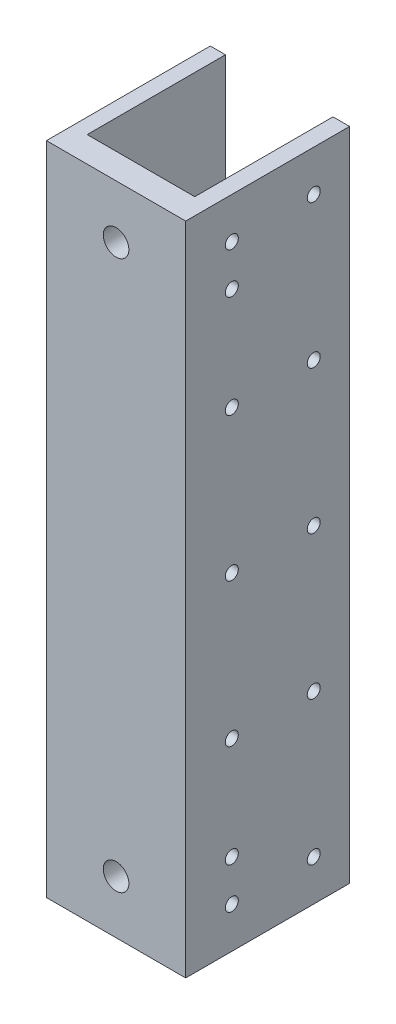
SolidWorks part; units mm, degrees
material "6061-T6 (SS)"
ref_plane "Front Plane" through (0, 0, 0) normal (0, 0, 1) x (1, 0, 0)
ref_plane "Top Plane" through (0, 0, 0) normal (0, 1, 0) x (1, 0, 0)
ref_plane "Right Plane" through (0, 0, 0) normal (1, 0, 0) x (0, 0, -1)
sketch "Sketch1" plane through (0, 0, 0) normal (0, 0, 1) x (1, 0, 0)
  line L1 (-43.18, -78.28) -> (0, -78.28)
  line L2 (-43.18, -78.28) -> (-43.18, 124.92)
  line L3 (-43.18, 124.92) -> (0, 124.92)
  line L4 (0, -78.28) -> (0, 124.92)
  dimension "D1" = 43.18
  dimension "D2" = 203.2
extrude "Boss-Extrude1" add sketch "Sketch1" along normal blind 50.8
sketch "Sketch2" plane through (0, 0, 50.8) normal (0, 0, 1) x (1, 0, 0)
  circle A0 centre (-21.59, 108.41) radius 3.9624
  circle A1 centre (-21.59, -61.77) radius 3.9624
  dimension "D3" = 170.18
  dimension "D6" = 7.9248
  dimension "D7" = 7.9248
  dimension "D1" = 16.51
  dimension "D2" = 21.59
  dimension "D4" = 16.51
  dimension "D5" = 21.59
sketch "Sketch3" plane through (0, 0, 0) normal (1, 0, 0) x (0, 0, -1)
  circle A0 centre (-36.5125, 99.52) radius 1.9812
  circle A1 centre (-36.5125, 23.32) radius 1.9812
  circle A2 centre (-36.5125, -52.88) radius 1.9812
  dimension "D7" = 3.9624
  dimension "D8" = 3.9624
  dimension "D9" = 3.9624
  dimension "D1" = 25.4
  dimension "D2" = 14.2875
  dimension "D3" = 76.2
  dimension "D4" = 25.4
  dimension "3" = 76.2
  dimension "D5" = 14.2875
  dimension "D6" = 14.2875
hole_wizard "3/8-16 Tapped Hole1" positions "Sketch5" profile "Sketch6" tap size "3/8-16" standard "ANSI Inch" end condition through all
sketch "Sketch5" plane through (0, 0, 50.8) normal (0, 0, 1) x (1, 0, 0)
  point P0 (-21.59, 108.41)
  point P3 (-21.59, -61.77)
sketch "Sketch6" plane through (-21.59, 108.41, 50.8) normal (1, 0, 0) x (0, -1, 0)
  line L0 (0, 0) -> (0, 50.8)
  line L1 (0, 50.8) -> (3.9687, 50.8)
  line L2 (3.9687, 50.8) -> (3.9687, 0)
  line L5 (3.9687, 0) -> (0, 0)
  line L11 (0, -6.35) -> (0, 107.95) construction
  dimension "Thru Tap Drill Dia." = 7.9375
  dimension "Thru Tap Drill Depth" = 50.8
cosmetic thread "Hole Thread1" parameters "D2"=9.525
cosmetic thread "Hole Thread2" parameters "D2"=9.525
hole_wizard "#10-32 Tapped Hole1" positions "Sketch8" profile "Sketch7" tap size "#10-32" standard "ANSI Inch" end condition through all
sketch "Sketch8" plane through (0, 0, 0) normal (1, 0, 0) x (0, 0, -1)
  point P0 (-36.5125, 99.52)
  point P3 (-36.5125, 23.32)
  point P6 (-36.5125, -52.88)
sketch "Sketch7" plane through (0, 99.52, 36.5125) normal (0, 1, 0) x (0, 0, -1)
  line L0 (0, 0) -> (0, 43.18)
  line L1 (0, 43.18) -> (2.0193, 43.18)
  line L2 (2.0193, 43.18) -> (2.0193, 0)
  line L5 (2.0193, 0) -> (0, 0)
  line L11 (0, -6.35) -> (0, 107.95) construction
  dimension "Thru Tap Drill Dia." = 4.0386
  dimension "Thru Tap Drill Depth" = 43.18
cosmetic thread "Hole Thread3" parameters "D2"=4.826
cosmetic thread "Hole Thread4" parameters "D2"=4.826
cosmetic thread "Hole Thread5" parameters "D2"=4.826
sketch "Sketch9" plane through (0, 124.92, 0) normal (0, 1, 0) x (1, 0, 0)
  line L1 (-38.481, 7.7343) -> (-5.1435, 7.7343)
  line L2 (-38.481, 7.7343) -> (-38.481, -42.8625)
  line L3 (-38.481, -42.8625) -> (-5.1435, -42.8625)
  line L4 (-5.1435, 7.7343) -> (-5.1435, -42.8625)
  dimension "D1" = 7.9375
  dimension "D2" = 33.3375
  dimension "D3" = 4.699
extrude "Cut-Extrude1" cut sketch "Sketch9" against normal through all contours L3 L4 L1 L2
hole_wizard "#10-32 Tapped Hole2" positions "Sketch10" profile "Sketch11" tap size "#10-32" standard "ANSI Inch"
sketch "Sketch10" plane through (3.175, 53.7921, -9.0871) normal (1, 0, 0) x (0, 0, -1)
  point P0 (284.6004, 58.4279)
  point P3 (310.0004, 58.4279)
  point P6 (284.6004, 13.9779)
  point P9 (310.0004, 13.9779)
  point P12 (284.6004, -30.4721)
  point P15 (284.6004, -74.9221)
  point P18 (310.0004, -74.9221)
  point P21 (284.6004, -119.3721)
  point P24 (310.0004, -119.3721)
  point P27 (-20.1996, 58.4279)
  point P30 (-45.5996, 58.4279)
  point P33 (-20.1996, 13.9779)
  point P36 (-45.5996, 13.9779)
  point P39 (-20.1996, -30.4721)
  point P42 (-20.1996, -74.9221)
  point P45 (-45.5996, -74.9221)
  point P48 (-45.5996, -119.3721)
  point P51 (-20.1996, -119.3721)
sketch "Sketch11" plane through (3.175, 112.22, -293.6875) normal (0, 1, 0) x (0, 0, -1)
  line L0 (0, 0) -> (0, 18.9933)
  line L1 (0, 18.9933) -> (2.0193, 17.78)
  line L2 (2.0193, 17.78) -> (2.0193, 0)
  line L3 (2.0193, 0) -> (0, 0)
  line L4 (0, 18.9933) -> (-2.0193, 17.78) construction
  line L5 (0, -6.35) -> (0, 107.95) construction
  dimension "Tap Drill Dia." = 4.0386
  dimension "Tap Drill Depth" = 17.78
  dimension "Drill Angle" = 118
cosmetic thread "Hole Thread6" parameters "D1"=8.3185, "D2"=4.826
cosmetic thread "Hole Thread7" parameters "D1"=8.3185, "D2"=4.826
cosmetic thread "Hole Thread8" parameters "D1"=8.3185, "D2"=4.826
cosmetic thread "Hole Thread9" parameters "D1"=8.3185, "D2"=4.826
cosmetic thread "Hole Thread10" parameters "D1"=8.3185, "D2"=4.826
cosmetic thread "Hole Thread11" parameters "D1"=8.3185, "D2"=4.826
cosmetic thread "Hole Thread12" parameters "D1"=8.3185, "D2"=4.826
cosmetic thread "Hole Thread13" parameters "D1"=8.3185, "D2"=4.826
cosmetic thread "Hole Thread14" parameters "D1"=8.3185, "D2"=4.826
hole_wizard "#10-32 Tapped Hole3" positions "Sketch12" profile "Sketch13" tap size "#10-32" standard "ANSI Inch"
sketch "Sketch12" plane through (3.175, -7.1522, -273.4879) normal (1, 0, 0) x (0, 0, 1)
  point P0 (284.6004, 58.4279)
  point P3 (310.0004, 58.4279)
  point P6 (284.6004, 13.9779)
  point P9 (310.0004, 13.9779)
  point P12 (284.6004, -30.4721)
  point P15 (284.6004, -74.9221)
  point P18 (310.0004, -74.9221)
  point P21 (284.6004, -119.3721)
  point P24 (310.0004, -119.3721)
  point P27 (-20.1996, 58.4279)
  point P30 (-45.5996, 58.4279)
  point P33 (-20.1996, 13.9779)
  point P36 (-45.5996, 13.9779)
  point P39 (-20.1996, -30.4721)
  point P42 (-20.1996, -74.9221)
  point P45 (-45.5996, -74.9221)
  point P48 (-45.5996, -119.3721)
  point P51 (-20.1996, -119.3721)
sketch "Sketch13" plane through (3.175, -65.58, 11.1125) normal (0, 1, 0) x (0, 0, -1)
  line L0 (0, 0) -> (0, 18.9933)
  line L1 (0, 18.9933) -> (2.0193, 17.78)
  line L2 (2.0193, 17.78) -> (2.0193, 0)
  line L3 (2.0193, 0) -> (0, 0)
  line L4 (0, 18.9933) -> (-2.0193, 17.78) construction
  line L5 (0, -6.35) -> (0, 107.95) construction
  dimension "Tap Drill Dia." = 4.0386
  dimension "Tap Drill Depth" = 17.78
  dimension "Drill Angle" = 118
